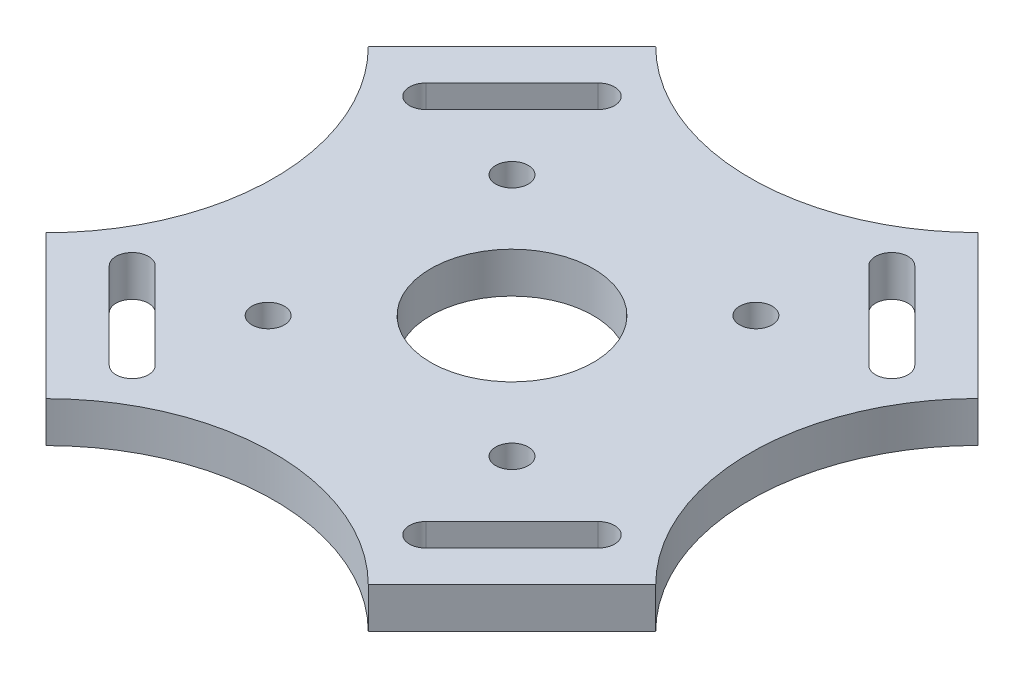
SolidWorks part; units mm, degrees
ref_plane "Front Plane" through (0, 0, 0) normal (0, 0, 1) x (1, 0, 0)
ref_plane "Top Plane" through (0, 0, 0) normal (0, 1, 0) x (1, 0, 0)
ref_plane "Right Plane" through (0, 0, 0) normal (1, 0, 0) x (0, 0, -1)
sketch "Sketch2" plane through (0, 0, 0) normal (0, 1, 0) x (1, 0, 0)
  line L1 (18.7842, 41.5533) -> (36.4619, 23.8757)
  line L3 (36.4619, -15.769) -> (18.7842, -33.4467)
  line L5 (-20.8442, -33.463) -> (-38.5218, -15.7853)
  line L7 (-38.5381, 23.8757) -> (-20.8605, 41.5533)
  line L8 (-20.8605, 41.5533) -> (18.7842, -33.4467) construction
  line L9 (18.7842, 41.5533) -> (-20.8442, -33.463) construction
  line L10 (-33.2348, 18.5724) -> (-15.5572, 36.25) construction
  line L11 (-38.5381, 23.8757) -> (-33.2348, 18.5724) construction
  line L12 (-20.8605, 41.5533) -> (-15.5572, 36.25) construction
  line L13 (-19.0927, 32.7145) -> (-29.6993, 22.1079) construction
  line L14 (-17.6785, 31.3003) -> (-28.2851, 20.6937)
  line L15 (-20.5069, 34.1287) -> (-31.1135, 23.5221)
  line L16 (29.0373, 23.5221) -> (18.4306, 34.1287)
  line L17 (26.2088, 20.6937) -> (15.6022, 31.3003)
  line L18 (27.623, 22.1079) -> (17.0164, 32.7145) construction
  line L19 (18.4306, -26.0221) -> (29.0373, -15.4155)
  line L20 (15.6022, -23.1936) -> (26.2088, -12.587)
  line L21 (17.0164, -24.6078) -> (27.623, -14.0012) construction
  line L22 (-31.1135, -15.4155) -> (-20.5069, -26.0221)
  line L23 (-28.2851, -12.587) -> (-17.6785, -23.1936)
  line L24 (-29.6993, -14.0012) -> (-19.0927, -24.6078) construction
  line L26 (-16.0381, -10.9467) -> (13.9619, -10.9467) construction
  line L27 (-16.0381, -10.9467) -> (-16.0381, 19.0533) construction
  line L28 (-16.0381, 19.0533) -> (13.9619, 19.0533) construction
  line L29 (13.9619, -10.9467) -> (13.9619, 19.0533) construction
  line L30 (-1.0381, 4.0533) -> (-1.0118, 4.0797) construction
  line L31 (-1.0381, 4.0533) -> (-1.03, 4.0452) construction
  arc A0 (-20.8605, 41.5533) -> (18.7842, 41.5533) centre (-1.0381, 61.3757) ccw
  arc A1 (36.4619, 23.8757) -> (36.4619, -15.769) centre (56.2842, 4.0533) ccw
  arc A2 (-20.8442, -33.463) -> (18.7842, -33.4467) centre (-1.0218, -53.2853) cw
  arc A3 (-38.5218, -15.7853) -> (-38.5381, 23.8757) centre (-58.3442, 4.037) ccw
  circle A4 centre (-33.2348, 18.5724) radius 5 construction
  circle A5 centre (-15.5572, 36.25) radius 5 construction
  arc A6 (-17.6785, 31.3003) -> (-20.5069, 34.1287) centre (-19.0927, 32.7145) ccw
  arc A7 (-31.1135, 23.5221) -> (-28.2851, 20.6937) centre (-29.6993, 22.1079) ccw
  arc A8 (26.2088, 20.6937) -> (29.0373, 23.5221) centre (27.623, 22.1079) ccw
  arc A9 (18.4306, 34.1287) -> (15.6022, 31.3003) centre (17.0164, 32.7145) ccw
  arc A10 (15.6022, -23.1936) -> (18.4306, -26.0221) centre (17.0164, -24.6078) ccw
  arc A11 (29.0373, -15.4155) -> (26.2088, -12.587) centre (27.623, -14.0012) ccw
  arc A12 (-28.2851, -12.587) -> (-31.1135, -15.4155) centre (-29.6993, -14.0012) ccw
  arc A13 (-20.5069, -26.0221) -> (-17.6785, -23.1936) centre (-19.0927, -24.6078) ccw
  circle A14 centre (-1.0381, 4.0533) radius 10
  circle A16 centre (-16.0381, 19.0533) radius 2
  circle A17 centre (13.9619, 19.0533) radius 2
  circle A18 centre (13.9619, -10.9467) radius 2
  circle A19 centre (-16.0381, -10.9467) radius 2
  point P18 (-24.396, 27.4112)
  point P28 (22.3197, 27.4112)
  point P35 (22.3197, -19.3045)
  point P42 (-24.396, -19.3045)
  point P47 (-1.0381, 4.0533)
  dimension "D8" = 28.033
  dimension "D9" = 28.033
  dimension "D4" = 28.033
  dimension "D5" = 28.033
  dimension "D10" = 10
  dimension "D11" = 10
  dimension "D12" = 2
  dimension "D14" = 20
  dimension "D15" = 4
  dimension "D16" = 4
  dimension "D17" = 4
  dimension "D18" = 4
  dimension "D1" = 25
  dimension "D2" = 7.5
  dimension "D3" = 25
  dimension "D6" = 25
  dimension "D7" = 25
  dimension "D13" = 4
extrude "Boss-Extrude1" add sketch "Sketch2" along normal blind 5 contours A3 L7 A0 L1 A1 L3 A2 L5
